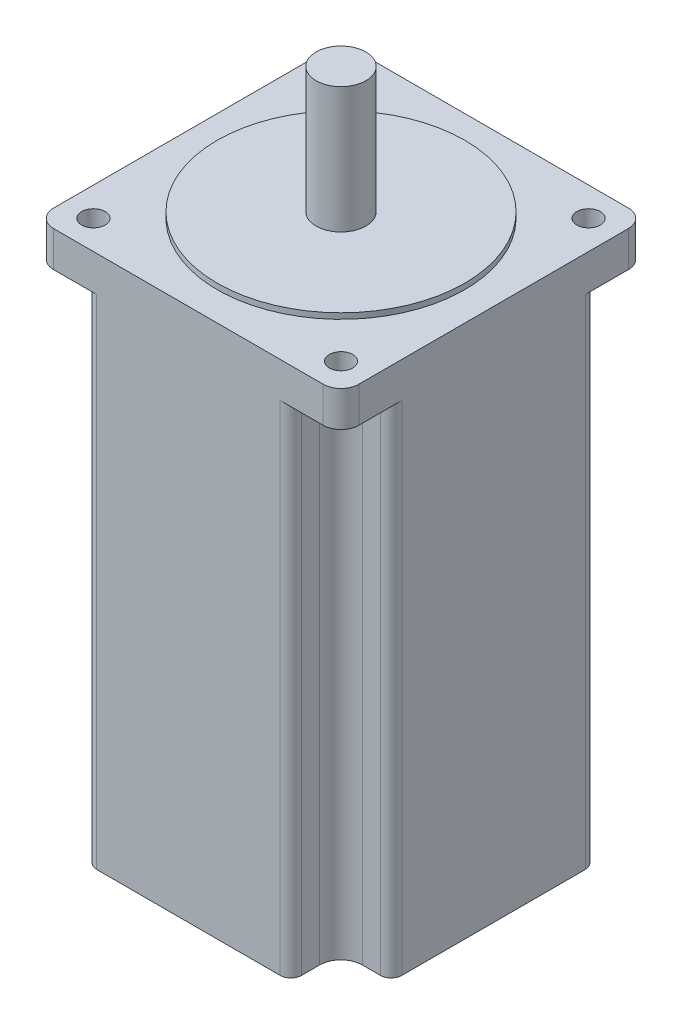
SolidWorks part; units mm, degrees
ref_plane "Front Plane" through (0, 0, 0) normal (0, 0, 1) x (1, 0, 0)
ref_plane "Top Plane" through (0, 0, 0) normal (0, 1, 0) x (1, 0, 0)
ref_plane "Right Plane" through (0, 0, 0) normal (1, 0, 0) x (0, 0, -1)
sketch "Sketch1" plane through (0, 0, 0) normal (0, 1, 0) x (1, 0, 0)
  line L1 (-34.8, -34.8) -> (34.8, -34.8) construction
  line L2 (-34.8, -34.8) -> (-34.8, 34.8) construction
  line L3 (-34.8, 34.8) -> (34.8, 34.8) construction
  line L4 (34.8, -34.8) -> (34.8, 34.8) construction
  line L5 (-34.8, -34.8) -> (34.8, 34.8) construction
  line L6 (-34.8, 34.8) -> (34.8, -34.8) construction
  line L7 (-42.9, -42.9) -> (42.9, -42.9)
  line L8 (-42.9, -42.9) -> (-42.9, 42.9)
  line L9 (-42.9, 42.9) -> (42.9, 42.9)
  line L10 (42.9, -42.9) -> (42.9, 42.9)
  line L11 (-42.9, -42.9) -> (42.9, 42.9) construction
  line L12 (-42.9, 42.9) -> (42.9, -42.9) construction
  circle A0 centre (-34.8, 34.8) radius 3.3
  circle A1 centre (34.8, 34.8) radius 3.3
  circle A2 centre (34.8, -34.8) radius 3.3
  circle A3 centre (-34.8, -34.8) radius 3.3
  point P0 (0, 0)
  point P6 (0, 0)
  dimension "D3" = 6.6
  dimension "D1" = 69.6
  dimension "D2" = 85.8
extrude "Boss-Extrude1" add sketch "Sketch1" against normal blind 150
sketch "Sketch2" plane through (0, 0, 0) normal (0, 1, 0) x (1, 0, 0)
  circle A0 centre (0, 0) radius 34.8
  dimension "D1" = 69.6
extrude "Boss-Extrude2" add sketch "Sketch2" along normal blind 1.6
sketch "Sketch3" plane through (0, 0, 0) normal (0, 1, 0) x (1, 0, 0)
  circle A0 centre (0, 0) radius 7
  dimension "D1" = 14
extrude "Boss-Extrude3" add sketch "Sketch3" along normal blind 37
sketch "Sketch4" plane through (0, 0, 0) normal (0, 1, 0) x (1, 0, 0)
  line L0 (-34.8, 28.8) -> (-51.2951, 28.8)
  line L1 (-51.2951, 28.8) -> (-51.2951, 48.6622)
  line L2 (-51.2951, 48.6622) -> (-28.8, 48.6622)
  line L3 (-28.8, 48.6622) -> (-28.8, 34.8)
  line L4 (48.6622, 28.8) -> (34.8, 28.8)
  line L5 (48.6622, 51.2951) -> (48.6622, 28.8)
  line L6 (28.8, 51.2951) -> (48.6622, 51.2951)
  line L7 (28.8, 34.8) -> (28.8, 51.2951)
  line L8 (28.8, -48.6622) -> (28.8, -34.8)
  line L9 (51.2951, -48.6622) -> (28.8, -48.6622)
  line L10 (51.2951, -28.8) -> (51.2951, -48.6622)
  line L11 (34.8, -28.8) -> (51.2951, -28.8)
  line L12 (-48.6622, -28.8) -> (-34.8, -28.8)
  line L13 (-48.6622, -51.2951) -> (-48.6622, -28.8)
  line L14 (-28.8, -51.2951) -> (-48.6622, -51.2951)
  line L15 (-28.8, -34.8) -> (-28.8, -51.2951)
  arc A0 (-34.8, 28.8) -> (-28.8, 34.8) centre (-34.8, 34.8) ccw
  arc A1 (28.8, 34.8) -> (34.8, 28.8) centre (34.8, 34.8) ccw
  arc A2 (34.8, -28.8) -> (28.8, -34.8) centre (34.8, -34.8) ccw
  arc A3 (-28.8, -34.8) -> (-34.8, -28.8) centre (-34.8, -34.8) ccw
  point P28 (0, 0)
  dimension "D1" = 12
  dimension "D2" = 4
extrude "Cut-Extrude1" cut sketch "Sketch4" against normal blind 157 from offset 10 offset against normal yes
fillet "Fillet1" radius 5 4 edges at (42.9, -5, 42.9) (-42.9, -5, 42.9) (-42.9, -5, -42.9) (42.9, -5, -42.9)
fillet "Fillet2" radius 3 8 edges at (-42.9, -80, -28.8) (-28.8, -80, -42.9) (-42.9, -80, 28.8) (-28.8, -80, 42.9) (28.8, -80, 42.9) (42.9, -80, 28.8) (42.9, -80, -28.8) (28.8, -80, -42.9)
